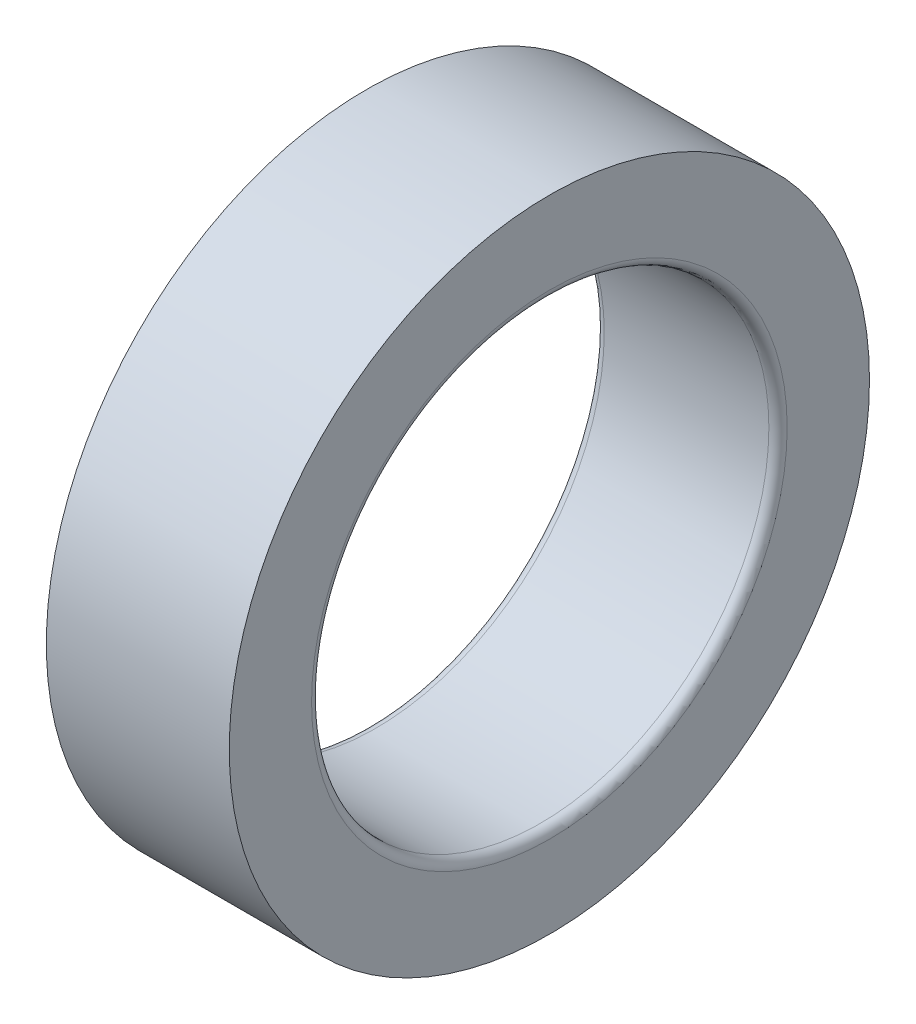
SolidWorks part; units mm, degrees
material "6061 Alloy"
ref_plane "Front Plane" through (0, 0, 0) normal (0, 0, 1) x (1, 0, 0)
ref_plane "Top Plane" through (0, 0, 0) normal (0, 1, 0) x (1, 0, 0)
ref_plane "Right Plane" through (0, 0, 0) normal (1, 0, 0) x (0, 0, -1)
sketch "Sketch2" plane through (0, 0, 0) normal (1, 0, 0) x (0, 0, -1)
  circle A0 centre (0, 0) radius 35
  circle A1 centre (0, 0) radius 25
  dimension "D1" = 70
  dimension "D2" = 50
extrude "Boss-Extrude1" add sketch "Sketch2" along normal blind 20
fillet "Fillet1" radius 1 2 edges at (0, 0, -25) (20, 0, -25)
